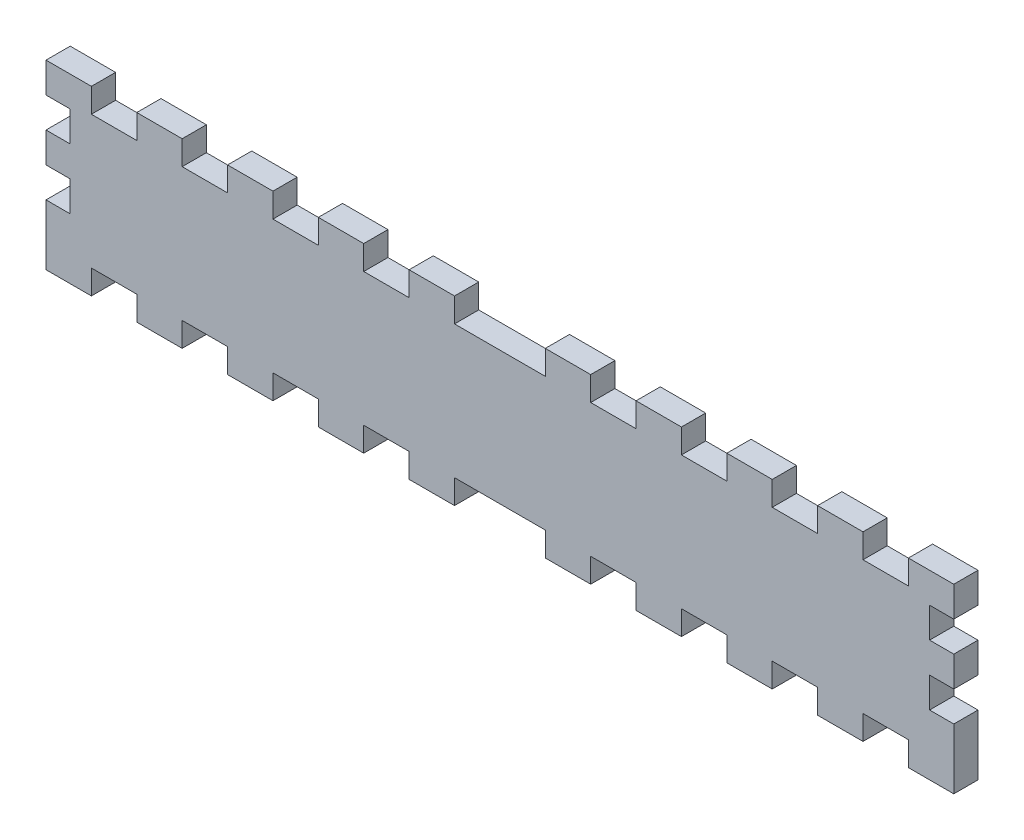
SolidWorks part; units mm, degrees
ref_plane "Plan de face" through (0, 0, 0) normal (0, 0, 1) x (1, 0, 0)
ref_plane "Plan de dessus" through (0, 0, 0) normal (0, 1, 0) x (1, 0, 0)
ref_plane "Plan de droite" through (0, 0, 0) normal (1, 0, 0) x (0, 0, -1)
sketch "Esquisse1" plane through (0, 0, 0) normal (0, 0, 1) x (1, 0, 0)
  line L1 (-150, -30) -> (150, -30)
  line L2 (-150, -30) -> (-150, 30)
  line L3 (-150, 30) -> (150, 30)
  line L4 (150, -30) -> (150, 30)
  line L5 (-150, -30) -> (150, 30) construction
  line L6 (-150, 30) -> (150, -30) construction
  point P0 (0, 0)
  dimension "D1" = 300
  dimension "D2" = 60
extrude "Boss.-Extru.1" add sketch "Esquisse1" along normal blind 8
sketch "Esquisse2" plane through (0, 0, 0) normal (0, 0, 1) x (1, 0, 0)
  line L0 (0, 0) -> (0, -7.6708) construction
  line L1 (-150, -30) -> (150, -30) construction
  line L2 (0, -30) -> (15, -30)
  line L4 (0, -22) -> (15, -22)
  line L5 (15, -30) -> (15, -22)
  line L22 (-120, -30) -> (-135, -30)
  line L23 (-135, -30) -> (-135, -22)
  line L24 (-120, -22) -> (-135, -22)
  line L25 (-120, -30) -> (-120, -22)
  line L26 (-90, -30) -> (-105, -30)
  line L27 (-105, -30) -> (-105, -22)
  line L28 (-90, -22) -> (-105, -22)
  line L29 (-90, -30) -> (-90, -22)
  line L30 (-60, -30) -> (-75, -30)
  line L31 (-75, -30) -> (-75, -22)
  line L32 (-60, -22) -> (-75, -22)
  line L33 (-60, -30) -> (-60, -22)
  line L34 (-30, -30) -> (-45, -30)
  line L35 (-45, -30) -> (-45, -22)
  line L36 (-30, -22) -> (-45, -22)
  line L37 (-30, -30) -> (-30, -22)
  line L39 (0, -30) -> (-15, -30)
  line L41 (0, -22) -> (-15, -22)
  line L42 (-15, -30) -> (-15, -22)
  line L43 (120, -30) -> (120, -22)
  line L44 (120, -22) -> (135, -22)
  line L45 (135, -30) -> (135, -22)
  line L46 (120, -30) -> (135, -30)
  line L47 (90, -30) -> (90, -22)
  line L48 (90, -22) -> (105, -22)
  line L49 (105, -30) -> (105, -22)
  line L50 (90, -30) -> (105, -30)
  line L51 (60, -30) -> (60, -22)
  line L52 (60, -22) -> (75, -22)
  line L53 (75, -30) -> (75, -22)
  line L54 (60, -30) -> (75, -30)
  line L55 (30, -30) -> (30, -22)
  line L56 (30, -22) -> (45, -22)
  line L57 (45, -30) -> (45, -22)
  line L58 (30, -30) -> (45, -30)
  dimension "D1" = 15
  dimension "D2" = 8
extrude "Enlèv. mat.-Extru.1" cut sketch "Esquisse2" along normal blind 8
sketch "Esquisse3" plane through (0, 0, 0) normal (0, 0, 1) x (1, 0, 0)
  line L0 (-150, 30) -> (-150, -30) construction
  line L1 (-150, 20) -> (-142, 20)
  line L2 (-150, 20) -> (-150, 10)
  line L3 (-150, 10) -> (-142, 10)
  line L4 (-142, 20) -> (-142, 10)
  line L5 (150, 30) -> (-150, 30) construction
  line L6 (-150, 0) -> (-150, -10)
  line L7 (-150, 0) -> (-142, 0)
  line L8 (-142, 0) -> (-142, -10)
  line L9 (-150, -10) -> (-142, -10)
  dimension "D1" = 10
  dimension "D2" = 8
  dimension "D3" = 10
  dimension "D4" = 2
extrude "Enlèv. mat.-Extru.2" cut sketch "Esquisse3" along normal through all
mirror "Symétrie1" about plane through (0, 0, 0) normal (1, 0, 0) of "Enlèv. mat.-Extru.2"
mirror "Symétrie2" about plane through (0, 0, 0) normal (0, 1, 0) of "Enlèv. mat.-Extru.1"
